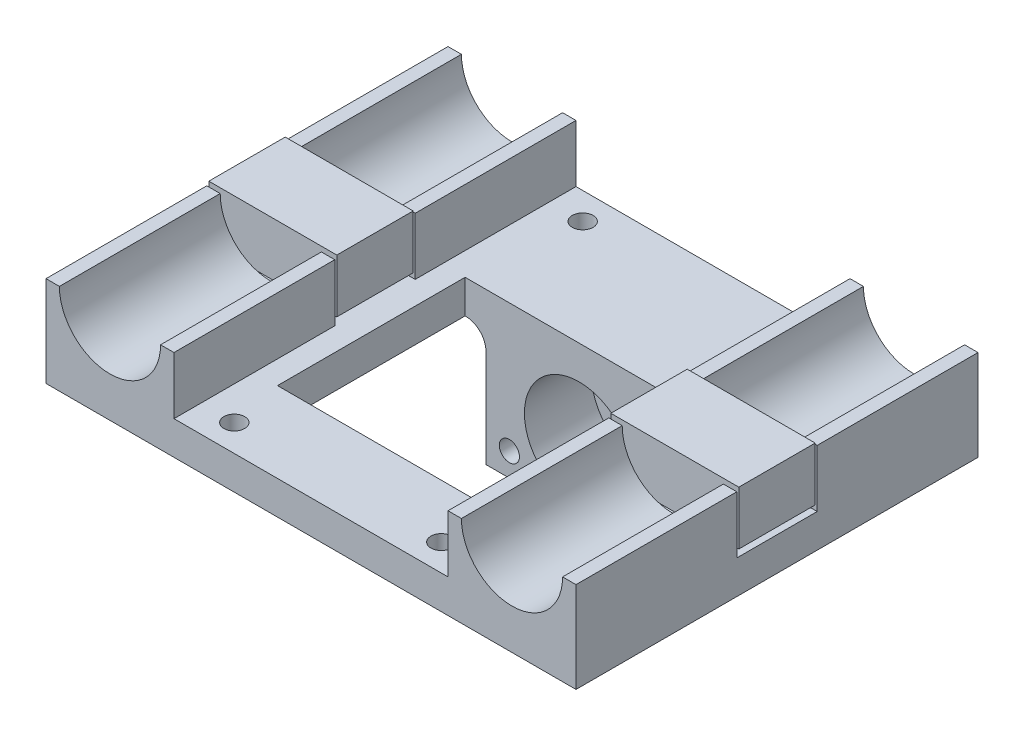
SolidWorks part; units mm, degrees
ref_plane "Front Plane" through (0, 0, 0) normal (0, 0, 1) x (1, 0, 0)
ref_plane "Top Plane" through (0, 0, 0) normal (0, 1, 0) x (1, 0, 0)
ref_plane "Right Plane" through (0, 0, 0) normal (1, 0, 0) x (0, 0, -1)
sketch "Sketch1" plane through (0, 0, 0) normal (0, 1, 0) x (1, 0, 0)
  line L1 (-39.55, 30) -> (39.55, 30)
  line L2 (-39.55, 30) -> (-39.55, -30)
  line L3 (-39.55, -30) -> (39.55, -30)
  line L4 (39.55, 30) -> (39.55, -30)
  dimension "D1" = 60
  dimension "D2" = 79.1
  dimension "D3" = 39.55
  dimension "D4" = 30
extrude "Boss-Extrude1" add sketch "Sketch1" along normal blind 5
sketch "Sketch2" plane through (0, 0, 30) normal (0, 0, 1) x (1, 0, 0)
  line L0 (-39.55, 5) -> (39.55, 5) construction
  line L1 (-39.55, 5) -> (-20.45, 5)
  line L2 (-39.55, 5) -> (-39.55, 13.55)
  line L3 (-39.55, 13.55) -> (-20.45, 13.55)
  line L4 (-20.45, 5) -> (-20.45, 13.55)
  circle A0 centre (-30, 13.55) radius 7.55
  line M3 (39.55, 5) -> (-39.55, 5)
  dimension "D3" = 15.1
  dimension "D1" = 19.1
  dimension "D2" = 8.55
  dimension "D4" = 30
extrude "Boss-Extrude2" add sketch "Sketch2" against normal blind 24 contours A0 L3 L2 L4 M3
mirror "Mirror1" about plane through (0, 0, 0) normal (0, 0, 1) of "Boss-Extrude2"
mirror "Mirror2" about plane through (0, 0, 0) normal (1, 0, 0) of "Mirror1", "Boss-Extrude2"
ref_plane "Plane1" through (-30, 0, 0) normal (-1, 0, 0) x (0, 0, 1)
ref_plane "Plane2" through (-22.275, 22.275, 0) normal (-0.7071, 0.7071, 0) x (0.7071, 0.7071, 0)
ref_plane "Plane3" through (0, 0, -10) normal (0, 0, -1) x (-1, 0, 0)
sketch "Sketch3" plane through (-22.275, 22.275, 0) normal (-0.7071, 0.7071, 0) x (0.7071, 0.7071, 0)
  line L0 (-27.9661, -30) -> (-18.3848, -30) construction
  line L2 (-24.4305, -6) -> (-24.4305, 6) construction
  circle A0 centre (-27.9305, -18) radius 1.75
  dimension "D1" = 3.5
  dimension "D2" = 12
  dimension "D3" = 3.5
sketch "Sketch10" plane through (0, 5, 0) normal (0, 1, 0) x (1, 0, 0)
  line L0 (-20.45, 6) -> (-20.45, 30) construction
  line L1 (20.45, 30) -> (-20.45, 30) construction
  line L2 (20.45, 6) -> (20.45, 30) construction
  line L3 (20.45, -6) -> (20.45, -30) construction
  line L4 (-20.45, -30) -> (20.45, -30) construction
  line L5 (-20.45, -6) -> (-20.45, -30) construction
  circle A0 centre (-15.45, -26) radius 1.55
  circle A1 centre (-15.45, 26) radius 1.55
  circle A2 centre (15.45, 26) radius 1.55
  circle A3 centre (15.45, -26) radius 1.55
  dimension "D1" = 3.1
  dimension "D2" = 5
  dimension "D3" = 4
  dimension "D4" = 4
  dimension "D5" = 5
  dimension "D6" = 5
  dimension "D7" = 4
  dimension "D8" = 5
  dimension "D9" = 4
extrude "Cut-Extrude7" cut sketch "Sketch10" against normal blind 8
sketch "Sketch11" plane through (0, 0, 0) normal (0, -1, 0) x (1, 0, 0)
  circle A0 centre (-15.45, 26) radius 3
  circle A1 centre (15.45, 26) radius 3
  circle A2 centre (15.45, -26) radius 3
  circle A3 centre (-15.45, -26) radius 3
  dimension "D1" = 6
extrude "Cut-Extrude8" cut sketch "Sketch11" against normal blind 1
sketch "Sketch12" plane through (0, 0, -10) normal (0, 0, 1) x (1, 0, 0)
  line L1 (-39.55, 0) -> (39.55, 0) construction
  line L2 (10.45, 0) -> (10.45, -8.153)
  line L3 (20.45, 5) -> (20.45, 13.55) construction
  line L4 (-10.45, 0) -> (10.45, 0)
  line L5 (-13.8923, 0) -> (13.8923, 0)
  line L6 (-13.8923, 0) -> (-13.8923, -17.653)
  line L7 (-13.8923, -17.653) -> (13.8923, -17.653)
  line L8 (13.8923, 0) -> (13.8923, -17.653)
  circle A0 centre (0, -8.153) radius 8.15
  circle A2 centre (0, -8.153) radius 15
  circle A3 centre (0, -8.153) radius 12
  circle A4 centre (0, 3.847) radius 1.5
  circle A5 centre (10.3923, -14.153) radius 1.5
  circle A6 centre (-10.3923, -14.153) radius 1.5
  point P22 (0, -8.153)
  dimension "D1" = 16.3
  dimension "D2" = 8.153
  dimension "D4" = 30
  dimension "D5" = 24
  dimension "D6" = 3
  dimension "D7" = 3.5
  dimension "D3" = 10
  dimension "D8" = 3.5
  dimension "D9" = 3.5
extrude "Boss-Extrude5" add sketch "Sketch12" against normal blind 10
sketch "Sketch13" plane through (0, 0, 0) normal (0, -1, 0) x (1, 0, 0)
  line L1 (-17, 18) -> (17, 18)
  line L2 (-17, 18) -> (-17, -10)
  line L3 (-17, -10) -> (17, -10)
  line L4 (17, 18) -> (17, -10)
  line L5 (-17, 18) -> (17, -10) construction
  line L6 (-17, -10) -> (17, 18) construction
  point P0 (0, 4)
  dimension "D1" = 34
  dimension "D2" = 28
extrude "Cut-Extrude9" cut sketch "Sketch13" against normal blind 10
fillet "Fillet2" radius 3 2 edges at (13.8923, 0, -15) (-13.8923, 0, -15)
ref_plane "Plane4" through (-15.7727, -15.7727, 0) normal (-0.7071, -0.7071, 0) x (-0.7071, 0.7071, 0)
sketch "Sketch15" plane through (-15.7727, -15.7727, 0) normal (-0.7071, -0.7071, 0) x (-0.7071, 0.7071, 0)
  line L0 (-2.6592, 20) -> (-2.6592, 10) construction
  line L1 (-5.6592, 15.3) -> (0.3408, 15.3)
  line L2 (-5.6592, 15.3) -> (-5.6592, 12.5)
  line L3 (-5.6592, 12.5) -> (0.3408, 12.5)
  line L4 (0.3408, 15.3) -> (0.3408, 12.5)
  line L5 (-5.6592, 15.3) -> (0.3408, 12.5) construction
  line L6 (-5.6592, 12.5) -> (0.3408, 15.3) construction
  line L7 (7.4525, 10) -> (-7.4525, 10) construction
  point P0 (-2.6592, 13.9)
  dimension "D1" = 6
  dimension "D2" = 2.8
  dimension "D3" = 2.5
extrude "Cut-Extrude12" cut sketch "Sketch15" against normal blind 8.2
mirror "Mirror3" about plane through (0, 0, 0) normal (1, 0, 0) of "Cut-Extrude12"
sketch "Sketch16" plane through (0, 0, 30) normal (0, 0, 1) x (1, 0, 0)
  line L8 (-13.8923, -17.653) -> (13.8923, -17.653)
  line L9 (13.8923, -17.653) -> (13.8923, -3)
  line L10 (16.8923, 0) -> (17, 0)
  line L11 (17, 0) -> (17, 5)
  line L12 (17, 5) -> (-17, 5)
  line L13 (-17, 5) -> (-17, 0)
  line L14 (-17, 0) -> (-16.8923, 0)
  line L15 (-13.8923, -3) -> (-13.8923, -17.653)
  line L16 (-13.8923, -17.653) -> (13.8923, -17.653)
  line L17 (13.8923, -17.653) -> (13.8923, -3)
  line L18 (16.8923, 0) -> (17, 0)
  line L19 (17, 0) -> (17, 5)
  line L20 (17, 5) -> (-17, 5)
  line L21 (-17, 5) -> (-17, 0)
  line L22 (-17, 0) -> (-16.8923, 0)
  line L23 (-13.8923, -3) -> (-13.8923, -17.653)
  circle A1 centre (0, -8.153) radius 8.15 construction
  circle A2 centre (0, -8.153) radius 8.15
  arc A5 (16.8923, 0) -> (13.8923, -3) centre (16.8923, -3) ccw
  arc A6 (-13.8923, -3) -> (-16.8923, 0) centre (-16.8923, -3) ccw
  arc A7 (16.8923, 0) -> (13.8923, -3) centre (16.8923, -3) ccw
  arc A8 (-13.8923, -3) -> (-16.8923, 0) centre (-16.8923, -3) ccw
  dimension "D1" = 0
ref_plane "Plane5" through (0, 6, 0) normal (0, 1, 0) x (1, 0, 0)
sketch "Sketch17" plane through (0, 6, 0) normal (0, 1, 0) x (1, 0, 0)
  line L0 (-20.45, 6) -> (-20.45, 30) construction
  line L1 (-39.55, 5.7) -> (-20.45, 5.7)
  line L2 (-39.55, 5.7) -> (-39.55, -5.7)
  line L3 (-39.55, -5.7) -> (-20.45, -5.7)
  line L4 (-20.45, 5.7) -> (-20.45, -5.7)
  line L5 (-39.55, 5.7) -> (-20.45, -5.7) construction
  line L6 (-39.55, -5.7) -> (-20.45, 5.7) construction
  line L7 (-39.55, 6) -> (-39.55, 30) construction
  line L8 (-20.45, 6) -> (-39.55, 6) construction
  line L9 (-20.45, -6) -> (-39.55, -6) construction
  line L10 (0, 0) -> (0, 11.2352) construction
  line L11 (39.55, -5.7) -> (20.45, 5.7) construction
  line L12 (39.55, 5.7) -> (20.45, -5.7) construction
  line L13 (20.45, 5.7) -> (20.45, -5.7)
  line L14 (39.55, -5.7) -> (20.45, -5.7)
  line L15 (39.55, 5.7) -> (39.55, -5.7)
  line L16 (39.55, 5.7) -> (20.45, 5.7)
  point P0 (-30, 0)
  point P20 (30, 0)
  dimension "D1" = 0.3
  dimension "D2" = 0.3
extrude "Boss-Extrude6" add sketch "Sketch17" along normal blind 8 separate body
ref_plane "Plane6" through (0, -1, 0) normal (0, -1, 0) x (-1, 0, 0)
sketch "Sketch18" plane through (0, -1, 0) normal (0, -1, 0) x (-1, 0, 0)
  line L1 (-13.8923, 29.9705) -> (13.8923, 29.9705)
  line L2 (-13.8923, 29.9705) -> (-13.8923, 20.6)
  line L3 (-13.8923, 20.6) -> (13.8923, 20.6)
  line L4 (13.8923, 29.9705) -> (13.8923, 20.6)
  line L5 (-13.8923, 29.9705) -> (13.8923, 20.6) construction
  line L6 (-13.8923, 20.6) -> (13.8923, 29.9705) construction
  line L8 (16.8923, 20) -> (-16.8923, 20) construction
  line L9 (13.8923, 20) -> (13.8923, 15.3) construction
  line L10 (-13.8923, 20) -> (-13.8923, 15.3) construction
  point P0 (0, 25.2852)
  dimension "D1" = 0.6
extrude "Boss-Extrude7" add sketch "Sketch18" along normal up to surface (16.653 mm away) separate body up to face at (0, -17.653, -14.2667)
